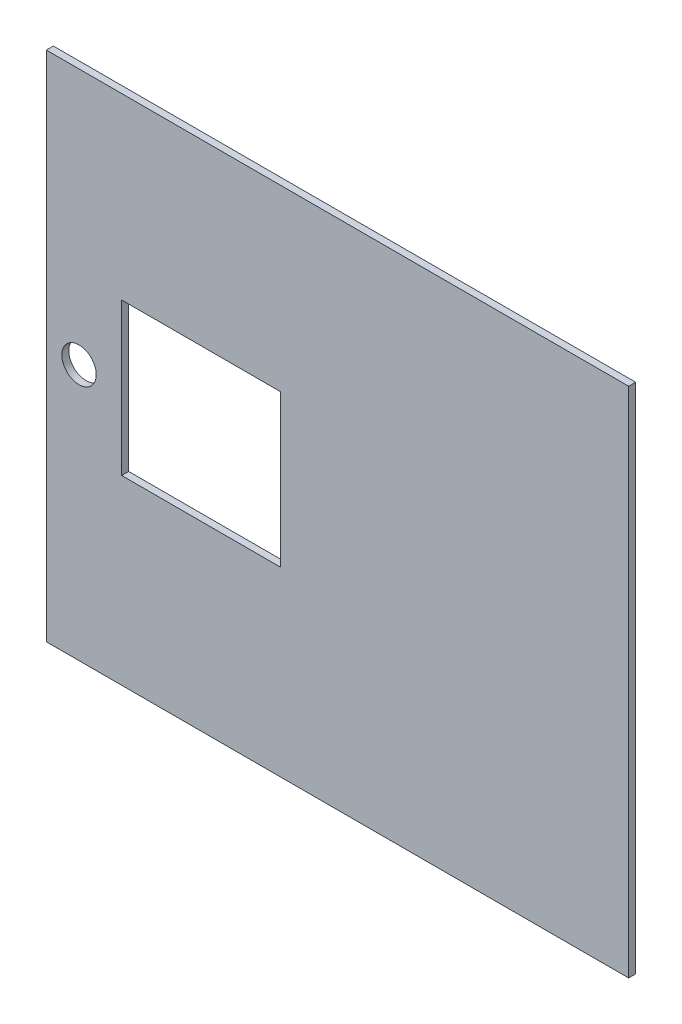
SolidWorks part; units mm, degrees
ref_plane "Top plane" through (0, 0, 0) normal (0, 0, 1) x (1, 0, 0)
ref_plane "Right plane" through (0, 0, 0) normal (0, 1, 0) x (1, 0, 0)
ref_plane "Front plane" through (0, 0, 0) normal (1, 0, 0) x (0, 0, -1)
sketch "Sketch1" plane through (0, 0, 0) normal (0, 0, 1) x (1, 0, 0)
  line L1 (-96.7999, 197.9066) -> (153.2001, 197.9066)
  line L2 (-96.7999, 197.9066) -> (-96.7999, -22.0934)
  line L3 (-96.7999, -22.0934) -> (153.2001, -22.0934)
  line L4 (153.2001, 197.9066) -> (153.2001, -22.0934)
  line L5 (-96.7999, 197.9066) -> (153.2001, -22.0934) construction
  line L6 (-96.7999, -22.0934) -> (153.2001, 197.9066) construction
  point P0 (28.2001, 87.9066)
  dimension "D1" = 220
  dimension "D2" = 250
extrude "Boss-Extrude1" add sketch "Sketch1" along normal blind 3
sketch "Sketch2" plane through (0, 0, 0) normal (0, 0, -1) x (-1, 0, 0)
  line L1 (-3.7984, 121.1493) -> (64.4442, 121.1493)
  line L2 (-3.7984, 121.1493) -> (-3.7984, 55.9066)
  line L3 (-3.7984, 55.9066) -> (64.4442, 55.9066)
  line L4 (64.4442, 121.1493) -> (64.4442, 55.9066)
extrude "Cut-Extrude1" cut sketch "Sketch2" against normal blind 3
sketch "Sketch3" plane through (0, 0, 0) normal (0, 0, -1) x (-1, 0, 0)
  circle A0 centre (82.7641, 87.9066) radius 7.392
extrude "Cut-Extrude2" cut sketch "Sketch3" against normal blind 10
